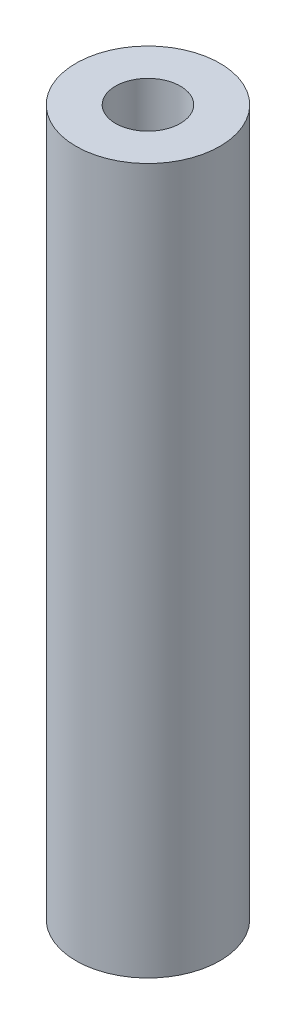
SolidWorks part; units mm, degrees
material "6061-T6 (SS)"
ref_plane "Alzado" through (0, 0, 0) normal (0, 0, 1) x (1, 0, 0)
ref_plane "Planta" through (0, 0, 0) normal (0, 1, 0) x (1, 0, 0)
ref_plane "Vista lateral" through (0, 0, 0) normal (1, 0, 0) x (0, 0, -1)
sketch "Croquis1" plane through (0, 0, 0) normal (0, 1, 0) x (1, 0, 0)
  circle A0 centre (0, 0) radius 5
  dimension "D1" = 10
extrude "Saliente-Extruir1" add sketch "Croquis1" along normal mid plane 49
hole_wizard "Taladro de margen para M41" positions "Croquis2" profile "Croquis3" hole size "M4" standard "Ansi Metric" end condition through all
sketch "Croquis2" plane through (0, 24.5, 0) normal (0, 1, 0) x (1, 0, 0)
  point P0 (0, 0)
sketch "Croquis3" plane through (0, 24.5, 0) normal (1, 0, 0) x (0, 0, 1)
  line L0 (0, 0) -> (0, 49)
  line L1 (0, 49) -> (2.25, 49)
  line L2 (2.25, 49) -> (2.25, 0)
  line L5 (2.25, 0) -> (0, 0)
  line L11 (0, -6.35) -> (0, 107.95) construction
  dimension "Diámetro de taladro hasta el siguiente" = 4.5
  dimension "Profundidad de taladro hasta el siguiente" = 49
